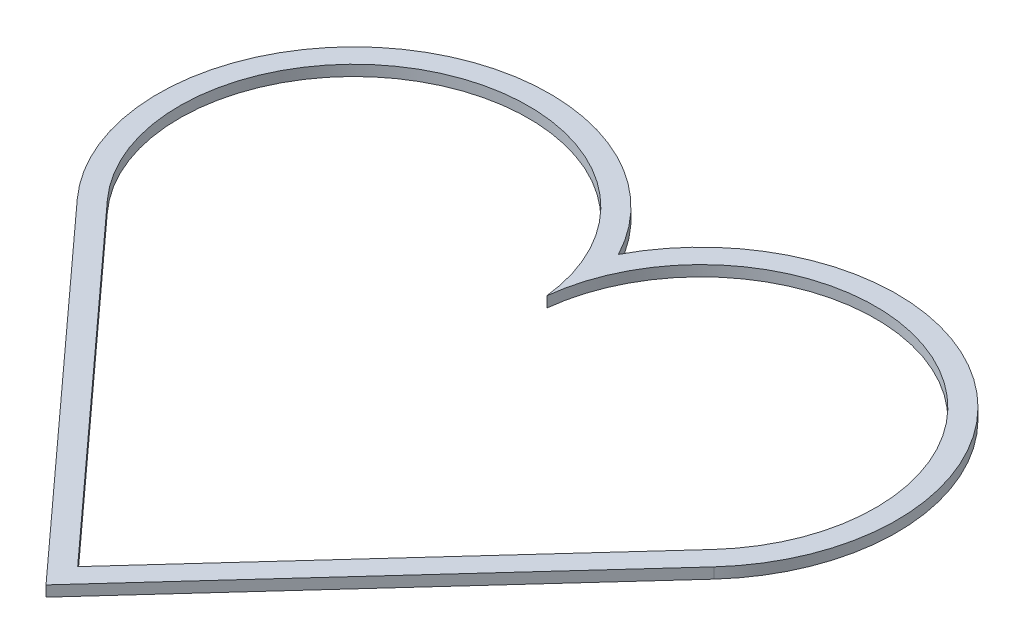
SolidWorks part; units mm, degrees
ref_plane "Front Plane" through (0, 0, 0) normal (0, 0, 1) x (1, 0, 0)
ref_plane "Top Plane" through (0, 0, 0) normal (0, 1, 0) x (1, 0, 0)
ref_plane "Right Plane" through (0, 0, 0) normal (1, 0, 0) x (0, 0, -1)
sketch "Sketch1" plane through (0, 0, 0) normal (0, 1, 0) x (1, 0, 0)
  line L0 (0, 0) -> (28.4077, 31.1959)
  line L1 (0, 0) -> (0, 44.0545) construction
  line L2 (0, 0) -> (-28.4077, 31.1959)
  line L3 (0, -2.9705) -> (29.8864, 29.8493)
  line L4 (0, -2.9705) -> (-29.8864, 29.8493)
  arc A0 (28.4077, 31.1959) -> (0, 44.0545) centre (16.2889, 42.2315) ccw
  arc A1 (-28.4077, 31.1959) -> (0, 44.0545) centre (-16.2889, 42.2315) cw
  arc A2 (29.8864, 29.8493) -> (0, 50.7688) centre (16.2889, 42.2315) ccw
  arc A3 (-29.8864, 29.8493) -> (0, 50.7688) centre (-16.2889, 42.2315) cw
  point P7 (0, 91.356)
  point P8 (-43.4024, 20.3005)
  point P9 (0, 55.1091)
  point P10 (-34.5403, 28.395)
  point P11 (0, 52.9731)
  point P18 (-29.3047, 30.7219)
  point P19 (0, 60.2447)
  point P20 (0, 45.4106)
  point P21 (-29.8864, 29.8493)
  dimension "D1" = 2
extrude "Boss-Extrude2" add sketch "Sketch1" along normal blind 1 contours A3 A2 L3 L4
